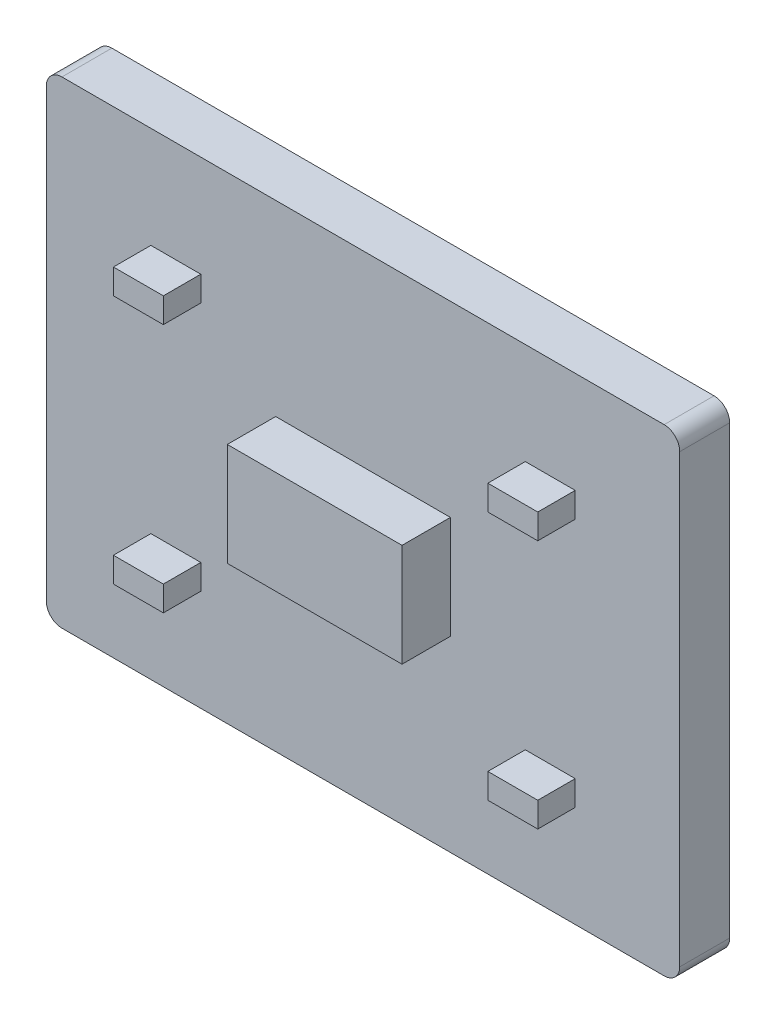
SolidWorks part; units mm, degrees
ref_plane "Front Plane" through (0, 0, 0) normal (0, 0, 1) x (1, 0, 0)
ref_plane "Top Plane" through (0, 0, 0) normal (0, 1, 0) x (1, 0, 0)
ref_plane "Right Plane" through (0, 0, 0) normal (1, 0, 0) x (0, 0, -1)
ref_plane "PZ_m2_00" through (0, 0, -2) normal (0, 0, 1) x (1, 0, 0)
sketch "PCB_Sk1" plane through (0, 0, -2) normal (0, 0, 1) x (1, 0, 0)
  line L0 (19.35, 3.35) -> (38.65, 3.35)
  line L1 (39.15, 3.85) -> (39.15, 18.15)
  line L2 (38.65, 18.65) -> (19.35, 18.65)
  line L3 (18.85, 18.15) -> (18.85, 3.85)
  arc A0 (18.85, 3.85) -> (19.35, 3.35) centre (19.35, 3.85) ccw
  arc A1 (38.65, 3.35) -> (39.15, 3.85) centre (38.65, 3.85) ccw
  arc A2 (39.15, 18.15) -> (38.65, 18.65) centre (38.65, 18.15) ccw
  arc A3 (19.35, 18.65) -> (18.85, 18.15) centre (19.35, 18.15) ccw
extrude "PCB" add sketch "PCB_Sk1" against normal blind 1.6
sketch "IC_Sk2" plane through (0, 0, -2) normal (0, 0, 1) x (1, 0, 0)
  line L0 (26.2, 9.35) -> (31.8, 9.35)
  line L1 (31.8, 9.35) -> (31.8, 12.65)
  line L2 (31.8, 12.65) -> (26.2, 12.65)
  line L3 (26.2, 12.65) -> (26.2, 9.35)
extrude "IC" add sketch "IC_Sk2" along normal blind 1.55
sketch "Parts_Sk3" plane through (0, 0, -2) normal (0, 0, 1) x (1, 0, 0)
  line L0 (22.2, 6.6) -> (23.8, 6.6)
  line L1 (23.8, 6.6) -> (23.8, 7.4)
  line L2 (23.8, 7.4) -> (22.2, 7.4)
  line L3 (22.2, 7.4) -> (22.2, 6.6)
  line L4 (22.2, 14.6) -> (23.8, 14.6)
  line L5 (23.8, 14.6) -> (23.8, 15.4)
  line L6 (23.8, 15.4) -> (22.2, 15.4)
  line L7 (22.2, 15.4) -> (22.2, 14.6)
  line L8 (34.2, 6.6) -> (35.8, 6.6)
  line L9 (35.8, 6.6) -> (35.8, 7.4)
  line L10 (35.8, 7.4) -> (34.2, 7.4)
  line L11 (34.2, 7.4) -> (34.2, 6.6)
  line L12 (34.2, 14.6) -> (35.8, 14.6)
  line L13 (35.8, 14.6) -> (35.8, 15.4)
  line L14 (35.8, 15.4) -> (34.2, 15.4)
  line L15 (34.2, 15.4) -> (34.2, 14.6)
extrude "Parts" add sketch "Parts_Sk3" along normal blind 1.2
